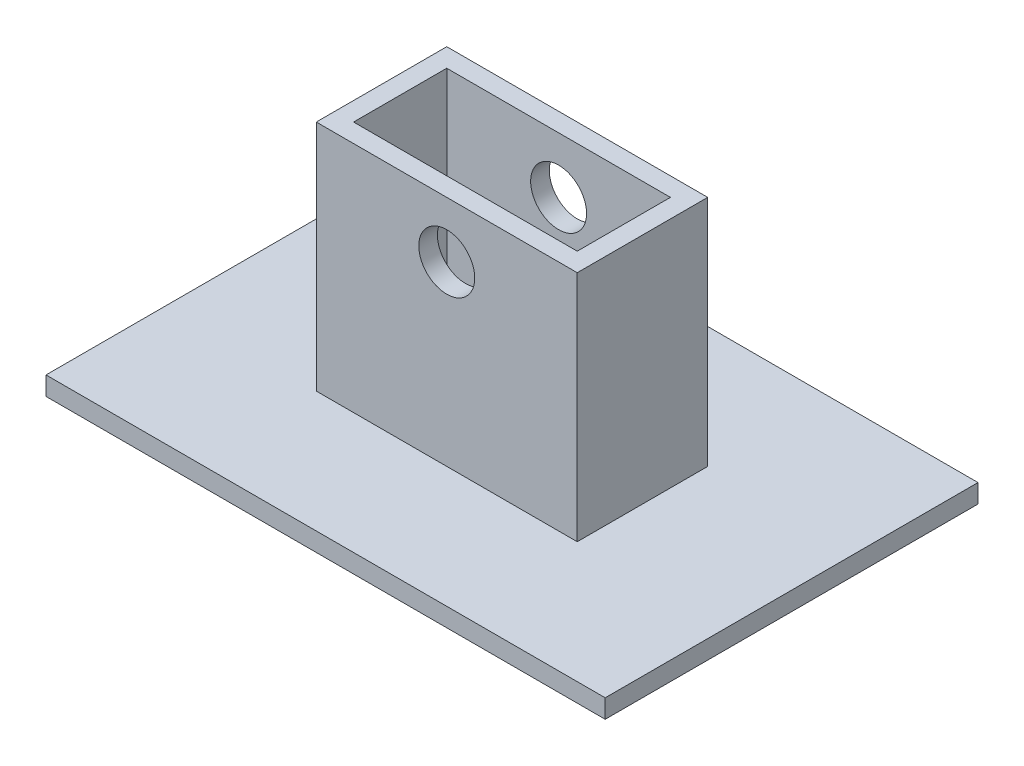
SolidWorks part; units mm, degrees
ref_plane "Front Plane" through (0, 0, 0) normal (0, 0, 1) x (1, 0, 0)
ref_plane "Top Plane" through (0, 0, 0) normal (0, 1, 0) x (1, 0, 0)
ref_plane "Right Plane" through (0, 0, 0) normal (1, 0, 0) x (0, 0, -1)
sketch "Sketch1" plane through (0, 0, 0) normal (0, 1, 0) x (1, 0, 0)
  line L1 (-38.1, 25.4) -> (38.1, 25.4)
  line L2 (-38.1, 25.4) -> (-38.1, -25.4)
  line L3 (-38.1, -25.4) -> (38.1, -25.4)
  line L4 (38.1, 25.4) -> (38.1, -25.4)
  dimension "D1" = 38.1
  dimension "D2" = 76.2
  dimension "D3" = 50.8
  dimension "D4" = 25.4
extrude "Boss-Extrude1" add sketch "Sketch1" along normal blind 2.54
sketch "Sketch2" plane through (0, 2.54, 0) normal (0, 1, 0) x (1, 0, 0)
  line L0 (-15.24, 6.35) -> (15.24, 6.35)
  line L1 (-17.78, 8.89) -> (17.78, 8.89)
  line L2 (-17.78, 8.89) -> (-17.78, -8.89)
  line L3 (-17.78, -8.89) -> (17.78, -8.89)
  line L4 (17.78, 8.89) -> (17.78, -8.89)
  line L5 (15.24, 6.35) -> (15.24, -6.35)
  line L6 (-15.24, -6.35) -> (15.24, -6.35)
  line L7 (-15.24, 6.35) -> (-15.24, -6.35)
  dimension "D1" = 17.78
  dimension "D2" = 35.56
  dimension "D3" = 17.78
  dimension "D4" = 8.89
  dimension "D5" = 2.54
extrude "Boss-Extrude2" add sketch "Sketch2" along normal blind 31.75
sketch "Sketch3" plane through (0, 0, 8.89) normal (0, 0, 1) x (1, 0, 0)
  line L0 (-17.78, 34.29) -> (-17.78, 2.54) construction
  line L1 (-17.78, 34.29) -> (17.78, 34.29) construction
  circle A0 centre (0, 26.67) radius 3.81
  dimension "D3" = 7.62
  dimension "D1" = 17.78
  dimension "D2" = 7.62
extrude "Cut-Extrude1" cut sketch "Sketch3" against normal blind 31.75
